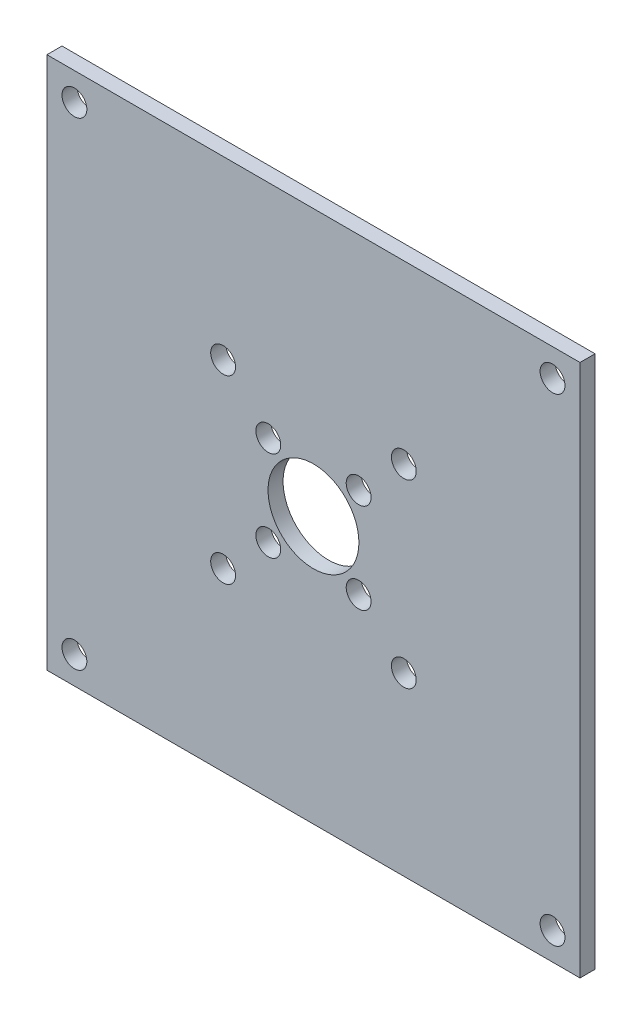
SolidWorks part; units mm, degrees
material "Acrylic (Medium-high impact)"
ref_plane "Front Plane" through (0, 0, 0) normal (0, 0, 1) x (1, 0, 0)
ref_plane "Top Plane" through (0, 0, 0) normal (0, 1, 0) x (1, 0, 0)
ref_plane "Right Plane" through (0, 0, 0) normal (1, 0, 0) x (0, 0, -1)
sketch "Sketch1" plane through (0, 0, 0) normal (0, 0, 1) x (1, 0, 0)
  line L0 (167.875, 167.875) -> (9.125, 9.125) construction
  line L1 (0, 0) -> (177, 0)
  line L2 (0, 0) -> (0, 177)
  line L3 (0, 177) -> (177, 177)
  line L4 (177, 0) -> (177, 177)
  line L5 (9.125, 9.125) -> (167.875, 9.125) construction
  line L6 (9.125, 9.125) -> (9.125, 167.875) construction
  line L7 (9.125, 167.875) -> (167.875, 167.875) construction
  line L8 (167.875, 9.125) -> (167.875, 167.875) construction
  line L9 (5, 9.125) -> (0, 9.125) construction
  line L10 (163.6459, 1.8) -> (159.4168, 9.125)
  line L11 (17.5832, 9.125) -> (13.3541, 16.45)
  line L12 (13.3541, 16.45) -> (4.8959, 16.45)
  line L13 (4.8959, 16.45) -> (0.6668, 9.125)
  line L14 (0.6668, 9.125) -> (4.8959, 1.8)
  line L15 (4.8959, 1.8) -> (13.3541, 1.8)
  line L16 (13.3541, 1.8) -> (17.5832, 9.125)
  line L17 (172.1041, 1.8) -> (163.6459, 1.8)
  line L18 (176.3332, 9.125) -> (172.1041, 1.8)
  line L19 (172.1041, 16.45) -> (176.3332, 9.125)
  line L20 (9.125, 88.5) -> (0, 88.5) construction
  line L21 (88.5, 9.125) -> (88.5, 0) construction
  line L22 (163.6459, 16.45) -> (172.1041, 16.45)
  line L23 (159.4168, 9.125) -> (163.6459, 16.45)
  line L24 (172.1041, 160.55) -> (176.3332, 167.875)
  line L25 (176.3332, 167.875) -> (172.1041, 175.2)
  line L26 (172.1041, 175.2) -> (163.6459, 175.2)
  line L27 (163.6459, 175.2) -> (159.4168, 167.875)
  line L28 (159.4168, 167.875) -> (163.6459, 160.55)
  line L29 (163.6459, 160.55) -> (172.1041, 160.55)
  line L30 (4.8959, 160.55) -> (0.6668, 167.875)
  line L31 (0.6668, 167.875) -> (4.8959, 175.2)
  line L32 (4.8959, 175.2) -> (13.3541, 175.2)
  line L33 (13.3541, 175.2) -> (17.5832, 167.875)
  line L34 (17.5832, 167.875) -> (13.3541, 160.55)
  line L35 (13.3541, 160.55) -> (4.8959, 160.55)
  line L36 (88.5, 9.125) -> (88.5, 73.5) construction
  line L37 (73.5, 103.5) -> (103.5, 103.5) construction
  line L38 (73.5, 103.5) -> (73.5, 73.5) construction
  line L39 (73.5, 73.5) -> (103.5, 73.5) construction
  line L40 (103.5, 103.5) -> (103.5, 73.5) construction
  line L41 (73.5, 88.5) -> (9.125, 88.5) construction
  line L42 (58.5, 88.5) -> (9.125, 88.5) construction
  line L43 (58.5, 58.5) -> (118.5, 58.5) construction
  line L44 (58.5, 58.5) -> (58.5, 118.5) construction
  line L45 (58.5, 118.5) -> (118.5, 118.5) construction
  line L46 (118.5, 58.5) -> (118.5, 118.5) construction
  line L47 (88.5, 58.5) -> (88.5, 9.125) construction
  circle A0 centre (9.125, 9.125) radius 4.125
  circle A1 centre (9.125, 9.125) radius 7.325 construction
  circle A2 centre (167.875, 9.125) radius 4.125
  circle A3 centre (167.875, 167.875) radius 4.125
  circle A4 centre (88.5, 88.5) radius 15.0882
  circle A5 centre (9.125, 167.875) radius 4.125
  circle A6 centre (73.5, 73.5) radius 4.125
  circle A7 centre (103.5, 73.5) radius 4.125
  circle A8 centre (73.5, 103.5) radius 4.125
  circle A9 centre (103.5, 103.5) radius 4.125
  circle A10 centre (58.5, 58.5) radius 4.125
  circle A11 centre (118.5, 58.5) radius 4.125
  circle A12 centre (58.5, 118.5) radius 4.125
  circle A13 centre (118.5, 118.5) radius 4.125
  point P47 (88.5, 167.875)
  point P48 (99.169, 99.169)
  point P58 (100.5832, 100.5832)
  dimension "D2" = 8.25
  dimension "D3" = 5
  dimension "D4" = 2
  dimension "D1" = 158.75
  dimension "D5" = 14.65
  dimension "D6" = 30
  dimension "D7" = 60
extrude "Boss-Extrude1" add sketch "Sketch1" along normal blind 5 contours L1 L4 L3 L2 A4 L10 L23 L22 L19 L18 L17 L16 L15 L14 L13 L12 L11 L29 L28 L27 L26 L25 L24 L34 L35 L30 L31 L32 L33 | L35 L34 L33 L32 L31 L30 A5 | L15 L16 L11 L12 L13 L14 A0 | L23 L10 L17 L18 L19 L22 A2 | L28 L29 L24 L25 L26 L27 A3
